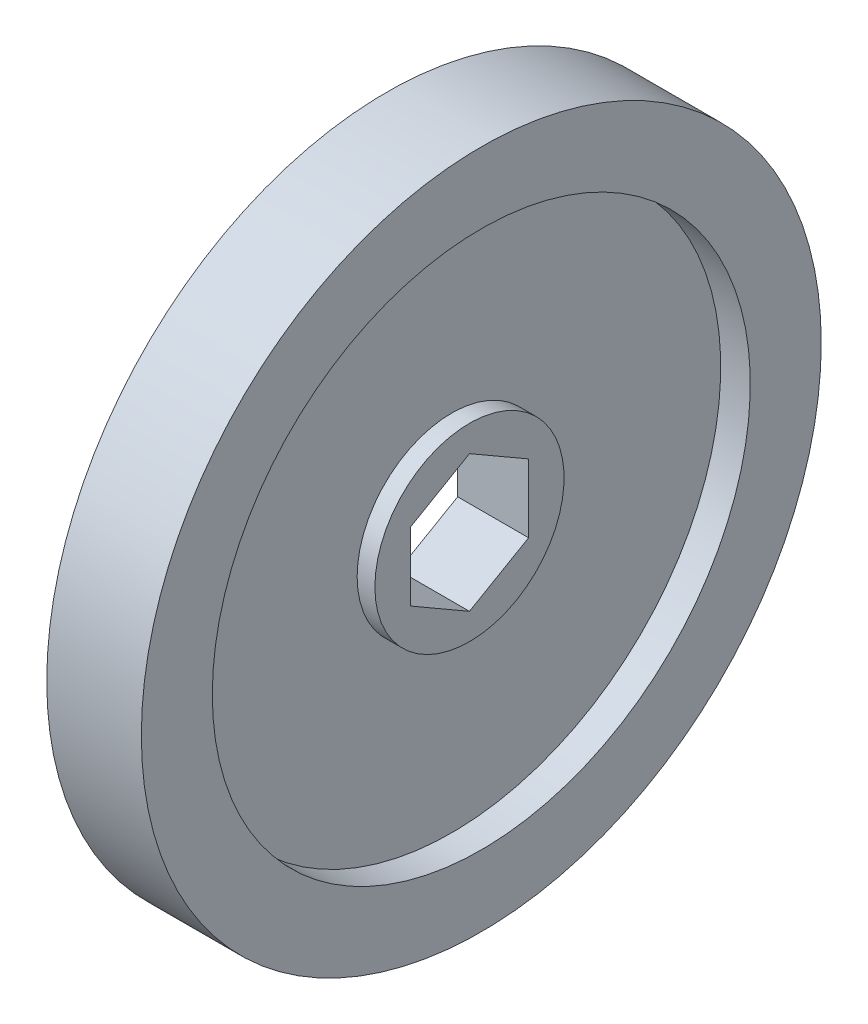
SolidWorks part; units mm, degrees
ref_plane "Plan de face" through (0, 0, 0) normal (0, 0, 1) x (1, 0, 0)
ref_plane "Plan de dessus" through (0, 0, 0) normal (0, 1, 0) x (1, 0, 0)
ref_plane "Plan de droite" through (0, 0, 0) normal (1, 0, 0) x (0, 0, -1)
sketch "Esquisse1" plane through (0, 0, 0) normal (0, 0, 1) x (1, 0, 0)
  line L0 (-12.566, 0) -> (17.5241, 0) construction
  line L1 (-5.08, 36.5125) -> (5.08, 36.5125)
  line L2 (5.08, 36.5125) -> (5.08, 28.8925)
  line L3 (5.08, 28.8925) -> (1.905, 28.8925)
  line L4 (1.905, 28.8925) -> (1.905, 10.16)
  line L5 (1.905, 10.16) -> (3.81, 10.16)
  line L6 (3.81, 10.16) -> (3.81, 0)
  line L7 (3.81, 0) -> (-3.81, 0)
  line L8 (0, 0) -> (0, 49.4244) construction
  line L9 (-3.81, 10.16) -> (-3.81, 0)
  line L10 (-1.905, 10.16) -> (-3.81, 10.16)
  line L11 (-1.905, 28.8925) -> (-1.905, 10.16)
  line L12 (-5.08, 28.8925) -> (-1.905, 28.8925)
  line L13 (-5.08, 36.5125) -> (-5.08, 28.8925)
  point P18 (0, 36.5125)
  dimension "D1" = 10.16
  dimension "D2" = 7.62
  dimension "D3" = 3.81
  dimension "D4" = 73.025
  dimension "D5" = 20.32
  dimension "D6" = 57.785
revolve "Révolution1" add sketch "Esquisse1" angle 360 about L0
sketch "Esquisse2" plane through (3.81, 0, 0) normal (1, 0, 0) x (0, 0, -1)
  line L1 (0, 7.3323) -> (-6.35, 3.6662)
  line L2 (-6.35, 3.6662) -> (-6.35, -3.6662)
  line L3 (-6.35, -3.6662) -> (0, -7.3323)
  line L4 (0, -7.3323) -> (6.35, -3.6662)
  line L5 (6.35, -3.6662) -> (6.35, 3.6662)
  line L6 (6.35, 3.6662) -> (0, 7.3323)
  circle A0 centre (0, 0) radius 6.35 construction
  dimension "D1" = 12.7
extrude "Enlèv. mat.-Extru.1" cut sketch "Esquisse2" against normal through all
